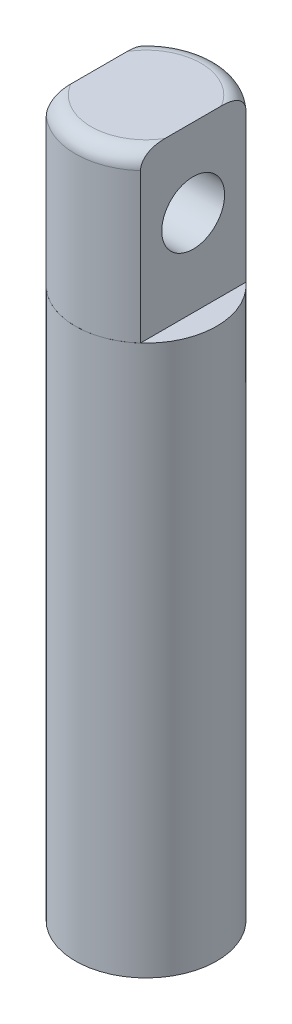
SolidWorks part; units mm, degrees
ref_plane "前视基准面" through (0, 0, 0) normal (0, 0, 1) x (1, 0, 0)
ref_plane "上视基准面" through (0, 0, 0) normal (0, 1, 0) x (1, 0, 0)
ref_plane "右视基准面" through (0, 0, 0) normal (1, 0, 0) x (0, 0, -1)
sketch "草图1" plane through (0, 0, 0) normal (0, 1, 0) x (1, 0, 0)
  circle A0 centre (0, 0) radius 4.5
  dimension "D1" = 9
extrude "凸台-拉伸1" add sketch "草图1" along normal blind 10.5
sketch "草图2" plane through (0, 10.5, 0) normal (0, 1, 0) x (1, 0, 0)
  line L0 (0, 4.5) -> (0, -4.5) construction
  line L1 (-3, 3.3541) -> (-3, -3.3541)
  line L2 (3, 3.3541) -> (3, -3.3541)
  circle A2 centre (0, 0) radius 4.5
  circle A3 centre (0, 0) radius 4.5
  circle M5 centre (0, 0) radius 4.5
  dimension "D2" = 6
  dimension "D1" = 0
extrude "切除-拉伸1" cut sketch "草图2" against normal blind 10.5 contours L1 M5 | L2 M5
sketch "草图3" plane through (-3, 0, 0) normal (-1, 0, 0) x (0, 0, 1)
  line L0 (0, 9.9132) -> (0, 0) construction
  line L1 (-3.3541, 0) -> (3.3541, 0) construction
  circle A0 centre (0, 5.5) radius 2
  dimension "D1" = 4
  dimension "D2" = 5.5
extrude "切除-拉伸2" cut sketch "草图3" against normal up to next
sketch "草图4" plane through (0, 0, 0) normal (0, -1, 0) x (1, 0, 0)
  circle A0 centre (0, 0) radius 4.5
  dimension "D1" = 9
extrude "凸台-拉伸2" add sketch "草图4" along normal blind 35 separate body
fillet "圆角1" radius 1 2 edges at (0, 10.5, -4.5) (0, 10.5, 4.5)
